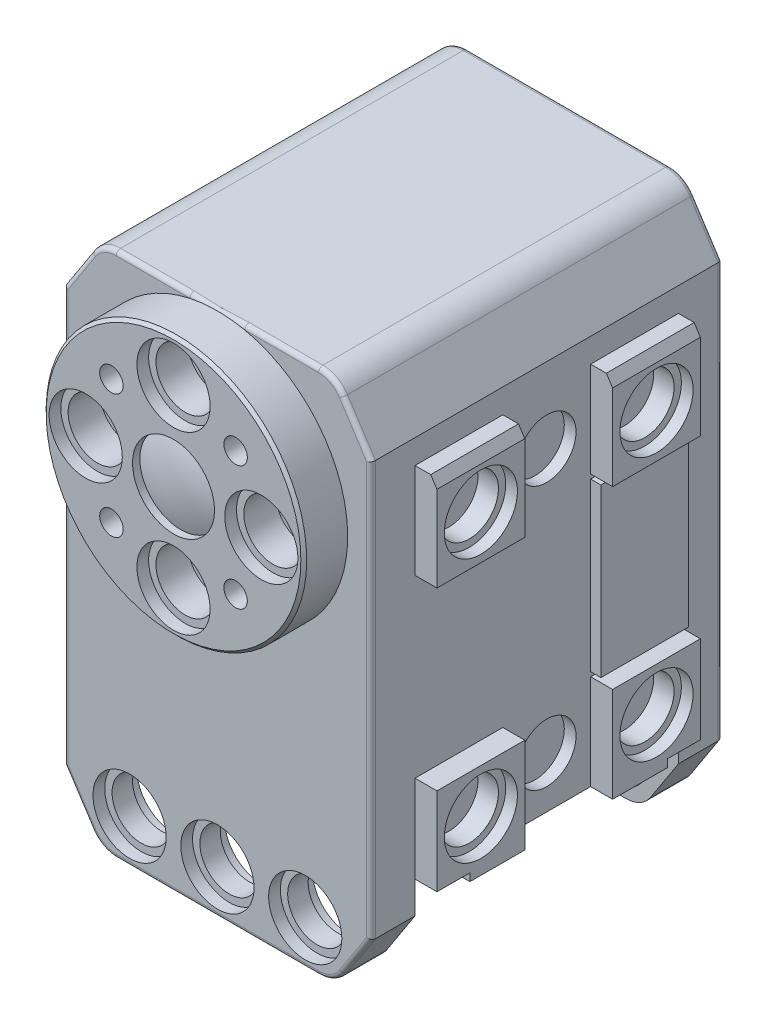
SolidWorks part; units mm, degrees
ref_plane "Front Plane" through (0, 0, 0) normal (0, 0, 1) x (1, 0, 0)
ref_plane "Top Plane" through (0, 0, 0) normal (0, 1, 0) x (1, 0, 0)
ref_plane "Right Plane" through (0, 0, 0) normal (1, 0, 0) x (0, 0, -1)
ref_plane "Plane1" through (0, 0, 0) normal (0, -1, 0) x (1, 0, 0)
sketch "Sketch1" plane through (0, 0, 0) normal (0, -1, 0) x (1, 0, 0)
  line L0 (0, 15) -> (0, 12)
  line L1 (0, 12) -> (8.9, 12)
  line L2 (8.9, 12) -> (8.9, 15)
  line L3 (8.9, 15) -> (2.8, 15)
  line L4 (2.8, 15) -> (2.8, 14.5)
  line L5 (0, 15.0001) -> (0, 12) construction
  arc A0 (2.8, 14.5) -> (0, 15) centre (0, 6.91) ccw
revolve "Revolve1" add sketch "Sketch1" angle 360 about L5
ref_plane "Plane2" through (0, 0, 12) normal (0, 0, 1) x (1, 0, 0)
sketch "Sketch2" plane through (0, 0, 12) normal (0, 0, 1) x (1, 0, 0)
  line L0 (10.5, -23.1503) -> (10.5, 5.1503)
  line L1 (10.5, 5.1503) -> (8, 9)
  line L2 (8, 9) -> (-8, 9)
  line L3 (-8, 9) -> (-10.5, 5.1503)
  line L4 (-10.5, 5.1503) -> (-10.5, -23.1503)
  line L5 (-10.5, -23.1503) -> (-8, -27)
  line L6 (-8, -27) -> (8, -27)
  line L7 (8, -27) -> (10.5, -23.1503)
extrude "Boss-Extrude1" add sketch "Sketch2" against normal blind 18.75
sketch "Sketch3" plane through (0, 0, -6.75) normal (0, 0, -1) x (-1, 0, 0)
  line L0 (-6, -21.5) -> (-10.5, -21.5)
  line L1 (-10.5, -21.5) -> (-10.5, -23.1503)
  line L2 (-10.5, -23.1503) -> (-8, -27)
  line L3 (-8, -27) -> (8, -27)
  line L4 (8, -27) -> (10.5, -23.1503)
  line L5 (10.5, -23.1503) -> (10.5, -21.5)
  line L6 (10.5, -21.5) -> (6, -21.5)
  line L7 (4, -22.5) -> (-4, -22.5)
  arc A0 (6, -21.5) -> (4, -22.5) centre (6, -24) ccw
  arc A1 (-4, -22.5) -> (-6, -21.5) centre (-6, -24) ccw
extrude "Cut-Extrude1" cut sketch "Sketch3" against normal blind 13.5
sketch "Sketch4" plane through (0, 0, 6.75) normal (0, 0, -1) x (-1, 0, 0)
  line L0 (-6, -20.975) -> (-10.5, -20.975)
  line L1 (-10.5, -20.975) -> (-10.5, -23.1503)
  line L2 (-10.5, -23.1503) -> (-8, -27)
  line L3 (-8, -27) -> (8, -27)
  line L4 (8, -27) -> (10.5, -23.1503)
  line L5 (10.5, -23.1503) -> (10.5, -20.975)
  line L6 (10.5, -20.975) -> (6, -20.975)
  line L7 (3.3731, -22.5) -> (-3.3731, -22.5)
  arc A0 (-3.3731, -22.5) -> (-6, -20.975) centre (-6, -24) ccw
  arc A1 (6, -20.975) -> (3.3731, -22.5) centre (6, -24) ccw
extrude "Cut-Extrude2" cut sketch "Sketch4" against normal blind 2.25
sketch "Sketch5" plane through (10.5, 0, 0) normal (1, 0, 0) x (0, 0, -1)
  line L0 (6.75, 5.1503) -> (6.75, -21.5)
  line L1 (6.75, -21.5) -> (3, -21.5)
  line L2 (3, -21.5) -> (3, 5.1503)
  line L3 (3, 5.1503) -> (6.75, 5.1503)
extrude "Boss-Extrude2" add sketch "Sketch5" along normal blind 1.5
sketch "Sketch6" plane through (10.5, 0, 0) normal (1, 0, 0) x (0, 0, -1)
  line L0 (-9, -20.975) -> (-9, -15)
  line L1 (-9, -15) -> (-3, -15)
  line L2 (-3, -15) -> (-3, -21.5)
  line L3 (-3, -21.5) -> (-6.75, -21.5)
  line L4 (-6.75, -21.5) -> (-6.75, -20.975)
  line L5 (-6.75, -20.975) -> (-9, -20.975)
extrude "Boss-Extrude3" add sketch "Sketch6" along normal blind 1.5
sketch "Sketch7" plane through (-10.5, 0, 0) normal (-1, 0, 0) x (0, 0, 1)
  line L0 (9, -15) -> (9, -20.975)
  line L1 (9, -20.975) -> (6.75, -20.975)
  line L2 (6.75, -20.975) -> (6.75, -21.5)
  line L3 (6.75, -21.5) -> (3, -21.5)
  line L4 (3, -21.5) -> (3, -15)
  line L5 (3, -15) -> (9, -15)
extrude "Boss-Extrude4" add sketch "Sketch7" along normal blind 1.5
sketch "Sketch8" plane through (-10.5, 0, 0) normal (-1, 0, 0) x (0, 0, 1)
  line L0 (-3, 5.1503) -> (-3, -21.5)
  line L1 (-3, -21.5) -> (-6.75, -21.5)
  line L2 (-6.75, -21.5) -> (-6.75, 5.1503)
  line L3 (-6.75, 5.1503) -> (-3, 5.1503)
extrude "Boss-Extrude5" add sketch "Sketch8" along normal blind 1.5
sketch "Sketch9" plane through (0, 5.1503, 0) normal (0, 1, 0) x (-1, 0, 0)
  line L0 (-12, -3) -> (-12, -6.75)
  line L1 (-12, -6.75) -> (-10.5, -6.75)
  line L2 (-10.5, -6.75) -> (-10.5, -3)
  line L3 (-10.5, -3) -> (-12, -3)
extrude "Cut-Extrude3" cut sketch "Sketch9" against normal blind 20.1503
sketch "Sketch10" plane through (0, 5.1503, 0) normal (0, 1, 0) x (-1, 0, 0)
  line L0 (10.5, -3) -> (10.5, -6.75)
  line L1 (10.5, -6.75) -> (12, -6.75)
  line L2 (12, -6.75) -> (12, -3)
  line L3 (12, -3) -> (10.5, -3)
extrude "Cut-Extrude4" cut sketch "Sketch10" against normal blind 20.1503
sketch "Sketch11" plane through (0, 0, -6.75) normal (0, 0, -1) x (-1, 0, 0)
  line L0 (12, -20.975) -> (6, -20.975)
  line L1 (3.3731, -22.5) -> (-3.3731, -22.5)
  line L2 (-6, -20.975) -> (-12, -20.975)
  line L3 (-12, -20.975) -> (-12, -15)
  line L4 (-12, -15) -> (-10.5, -15)
  line L5 (-10.5, -15) -> (-10.5, 5.1503)
  line L6 (-10.5, 5.1503) -> (-8, 9)
  line L7 (-8, 9) -> (8, 9)
  line L8 (8, 9) -> (10.5, 5.1503)
  line L9 (10.5, 5.1503) -> (10.5, -15)
  line L10 (10.5, -15) -> (12, -15)
  line L11 (12, -15) -> (12, -20.975)
  arc A0 (6, -20.975) -> (3.3731, -22.5) centre (6, -24) ccw
  arc A1 (-3.3731, -22.5) -> (-6, -20.975) centre (-6, -24) ccw
extrude "Boss-Extrude6" add sketch "Sketch11" along normal blind 2.25
sketch "Sketch12" plane through (0, 0, -9) normal (0, 0, -1) x (-1, 0, 0)
  line L0 (-8, 9) -> (8, 9)
  line L1 (8, 9) -> (10.5, 5.1503)
  line L2 (10.5, 5.1503) -> (10.5, -23.1503)
  line L3 (10.5, -23.1503) -> (8, -27)
  line L4 (8, -27) -> (-8, -27)
  line L5 (-8, -27) -> (-10.5, -23.1503)
  line L6 (-10.5, -23.1503) -> (-10.5, 5.1503)
  line L7 (-10.5, 5.1503) -> (-8, 9)
extrude "Boss-Extrude7" add sketch "Sketch12" along normal blind 3
sketch "Sketch13" plane through (0, 0, -9) normal (0, 0, 1) x (1, 0, 0)
  circle A0 centre (-6, -24) radius 2.5
extrude "Cut-Extrude5" cut sketch "Sketch13" against normal blind 0.8
sketch "Sketch14" plane through (0, 0, -12) normal (0, 0, -1) x (-1, 0, 0)
  circle A0 centre (6, -24) radius 2.5
extrude "Cut-Extrude6" cut sketch "Sketch14" against normal blind 0.8
sketch "Sketch15" plane through (0, 0, -11.2) normal (0, 0, -1) x (-1, 0, 0)
  circle A0 centre (6, -24) radius 2
extrude "Cut-Extrude7" cut sketch "Sketch15" against normal up to next
hole_wizard "M4x0.7 Tapped Hole1" positions "Sketch17" profile "Sketch16" tap size "M4x0.7" standard "ANSI Metric"
sketch "Sketch17" plane through (0, 0, -9) normal (0, 0, 1) x (1, 0, 0)
  point P0 (0, -24)
sketch "Sketch16" plane through (0, -24, -9) normal (1, 0, 0) x (0, -1, 0)
  line L0 (0, 0) -> (0, 2.2)
  line L1 (0, 2.2) -> (2.5, 2.2)
  line L2 (2.5, 2.2) -> (2.5, 1.4)
  line L3 (2.5, 1.4) -> (2, 1.4)
  line L4 (2, 1.4) -> (2, 0)
  line L5 (2, 0) -> (0, 0)
  line L10 (0, 2.2) -> (-2.5, 2.2) construction
  line L11 (0, -6.35) -> (0, 107.95) construction
  dimension "Tap Drill Dia." = 5
  dimension "Tap Drill Depth" = 2.2
  dimension "Thread Major Dia." = 4
  dimension "Thread Depth" = 1.4
  dimension "Drill Angle" = 180
sketch "Sketch18" plane through (0, 0, -9) normal (0, 0, 1) x (1, 0, 0)
  circle A0 centre (6, -24) radius 2.5
extrude "Cut-Extrude8" cut sketch "Sketch18" against normal blind 0.8
sketch "Sketch19" plane through (0, 0, -12) normal (0, 0, -1) x (-1, 0, 0)
  circle A0 centre (-6, -24) radius 2.5
extrude "Cut-Extrude9" cut sketch "Sketch19" against normal blind 0.8
sketch "Sketch20" plane through (0, 0, -11.2) normal (0, 0, -1) x (-1, 0, 0)
  circle A0 centre (-6, -24) radius 2
extrude "Cut-Extrude10" cut sketch "Sketch20" against normal up to next
sketch "Sketch21" plane through (10.5, 0, 0) normal (1, 0, 0) x (0, 0, -1)
  line L0 (9, -3) -> (3, -3)
  line L1 (3, -3) -> (3, 3.5)
  line L2 (3, 3.5) -> (9, 3.5)
  line L3 (9, 3.5) -> (9, -3)
extrude "Boss-Extrude8" add sketch "Sketch21" along normal blind 1.5
sketch "Sketch22" plane through (10.5, 0, 0) normal (1, 0, 0) x (0, 0, -1)
  line L0 (-9, 3.5) -> (-3, 3.5)
  line L1 (-3, 3.5) -> (-3, -3)
  line L2 (-3, -3) -> (-9, -3)
  line L3 (-9, -3) -> (-9, 3.5)
extrude "Boss-Extrude9" add sketch "Sketch22" along normal blind 1.5
sketch "Sketch23" plane through (10.5, 0, 0) normal (1, 0, 0) x (0, 0, -1)
  line L0 (9, -14.7) -> (3, -14.7)
  line L1 (3, -14.7) -> (3, -3.3)
  line L2 (3, -3.3) -> (9, -3.3)
  line L3 (9, -3.3) -> (9, -14.7)
extrude "Boss-Extrude10" add sketch "Sketch23" along normal blind 0.7
sketch "Sketch24" plane through (-10.5, 0, 0) normal (-1, 0, 0) x (0, 0, 1)
  line L0 (-9, 3.5) -> (-3, 3.5)
  line L1 (-3, 3.5) -> (-3, -3)
  line L2 (-3, -3) -> (-9, -3)
  line L3 (-9, -3) -> (-9, 3.5)
extrude "Boss-Extrude11" add sketch "Sketch24" along normal blind 1.5
sketch "Sketch25" plane through (-10.5, 0, 0) normal (-1, 0, 0) x (0, 0, 1)
  line L0 (9, -3) -> (3, -3)
  line L1 (3, -3) -> (3, 3.5)
  line L2 (3, 3.5) -> (9, 3.5)
  line L3 (9, 3.5) -> (9, -3)
extrude "Boss-Extrude12" add sketch "Sketch25" along normal blind 1.5
sketch "Sketch26" plane through (-10.5, 0, 0) normal (-1, 0, 0) x (0, 0, 1)
  line L0 (-9, -3.3) -> (-3, -3.3)
  line L1 (-3, -3.3) -> (-3, -14.7)
  line L2 (-3, -14.7) -> (-9, -14.7)
  line L3 (-9, -14.7) -> (-9, -3.3)
extrude "Boss-Extrude13" add sketch "Sketch26" along normal blind 0.7
ref_plane "Plane3" through (0, -24, 0) normal (0, 1, 0) x (1, 0, 0)
sketch "Sketch27" plane through (0, -24, 0) normal (0, 1, 0) x (1, 0, 0)
  line L0 (8.5, -9) -> (6, -9)
  line L1 (6, -9) -> (6, -12)
  line L2 (6, -12) -> (8.5, -12)
  line L3 (8.5, -12) -> (8.5, -11.2)
  line L4 (8.5, -11.2) -> (8, -11.2)
  line L5 (8, -11.2) -> (8, -9.8)
  line L6 (8, -9.8) -> (8.5, -9.8)
  line L7 (8.5, -9.8) -> (8.5, -9)
  line L8 (6, -9) -> (6, -12) construction
revolve "Cut-Revolve1" cut sketch "Sketch27" angle 360 about L8
sketch "Sketch28" plane through (0, -24, 0) normal (0, 1, 0) x (1, 0, 0)
  line L0 (-3.5, -9) -> (-6, -9)
  line L1 (-6, -9) -> (-6, -12)
  line L2 (-6, -12) -> (-3.5, -12)
  line L3 (-3.5, -12) -> (-3.5, -11.2)
  line L4 (-3.5, -11.2) -> (-4, -11.2)
  line L5 (-4, -11.2) -> (-4, -9.8)
  line L6 (-4, -9.8) -> (-3.5, -9.8)
  line L7 (-3.5, -9.8) -> (-3.5, -9)
  line L8 (-6, -9) -> (-6, -12) construction
revolve "Cut-Revolve2" cut sketch "Sketch28" angle 360 about L8
sketch "Sketch29" plane through (0, -24, 0) normal (0, 1, 0) x (1, 0, 0)
  line L0 (2.5, -9) -> (0, -9)
  line L1 (0, -9) -> (0, -12)
  line L2 (0, -12) -> (2.5, -12)
  line L3 (2.5, -12) -> (2.5, -11.2)
  line L4 (2.5, -11.2) -> (2, -11.2)
  line L5 (2, -11.2) -> (2, -9.8)
  line L6 (2, -9.8) -> (2.5, -9.8)
  line L7 (2.5, -9.8) -> (2.5, -9)
  line L8 (0, -9) -> (0, -12) construction
revolve "Cut-Revolve3" cut sketch "Sketch29" angle 360 about L8
hole_wizard "CBORE for M3.5 Hex Head Machine Screw1" positions "Sketch31" profile "Sketch30" counterbore size "M3.5" standard "ANSI Metric"
sketch "Sketch31" plane through (0, 0, -12) normal (0, 0, -1) x (-1, 0, 0)
  point P0 (6, 0)
  point P1 (0, 0)
  point P2 (-6, 0)
sketch "Sketch30" plane through (-6, 0, -12) normal (1, 0, 0) x (0, 1, 0)
  line L0 (0, 0) -> (0, 3)
  line L1 (0, 3) -> (2, 3)
  line L2 (2, 3) -> (2, 0.8)
  line L3 (2, 0.8) -> (2.5, 0.8)
  line L4 (2.5, 0.8) -> (2.5, 0)
  line L5 (2.5, 0) -> (0, 0)
  line L10 (0, 3) -> (-2, 3) construction
  line L11 (0, -6.35) -> (0, 107.95) construction
  dimension "Hole Dia." = 4
  dimension "Hole Depth" = 3
  dimension "C'Bore Dia." = 5
  dimension "C'Bore Depth" = 0.8
  dimension "Drill Angle" = 180
hole_wizard "Ø4.0 (4) Diameter Hole1" positions "Sketch33" profile "Sketch32" hole size "Ø4.0" standard "ANSI Metric"
sketch "Sketch33" plane through (-10.5, 0, 0) normal (-1, 0, 0) x (0, 0, 1)
  point P0 (0, 0)
  point P1 (0, -18)
sketch "Sketch32" plane through (-10.5, 0, 0) normal (0, 1, 0) x (0, 0, 1)
  line L0 (0, 0) -> (0, 0.8)
  line L1 (0, 0.8) -> (2, 0.8)
  line L2 (2, 0.8) -> (2, 0)
  line L5 (2, 0) -> (0, 0)
  line L10 (0, 0.8) -> (-2, 0.8) construction
  line L11 (0, -6.35) -> (0, 107.95) construction
  dimension "Hole Dia." = 4
  dimension "Hole Depth" = 0.8
  dimension "Drill Angle" = 180
hole_wizard "Ø4.0 (4) Diameter Hole2" positions "Sketch35" profile "Sketch34" hole size "Ø4.0" standard "ANSI Metric"
sketch "Sketch35" plane through (10.5, 0, 0) normal (1, 0, 0) x (0, 0, -1)
  point P0 (0, 0)
  point P1 (0, -18)
sketch "Sketch34" plane through (10.5, 0, 0) normal (0, 1, 0) x (0, 0, -1)
  line L0 (0, 0) -> (0, 0.8)
  line L1 (0, 0.8) -> (2, 0.8)
  line L2 (2, 0.8) -> (2, 0)
  line L5 (2, 0) -> (0, 0)
  line L10 (0, 0.8) -> (-2, 0.8) construction
  line L11 (0, -6.35) -> (0, 107.95) construction
  dimension "Hole Dia." = 4
  dimension "Hole Depth" = 0.8
  dimension "Drill Angle" = 180
hole_wizard "CBORE for M3.5 Hex Head Machine Screw2" positions "Sketch37" profile "Sketch36" counterbore size "M3.5" standard "ANSI Metric"
sketch "Sketch37" plane through (-12, 0, 0) normal (-1, 0, 0) x (0, 0, 1)
  point P0 (6, -18)
  point P1 (-6, -18)
  point P2 (-6, 0)
  point P3 (6, 0)
sketch "Sketch36" plane through (-12, -18, 6) normal (0, 1, 0) x (0, 0, 1)
  line L0 (0, 0) -> (0, 2.2)
  line L1 (0, 2.2) -> (2, 2.2)
  line L2 (2, 2.2) -> (2, 0.8)
  line L3 (2, 0.8) -> (2.5, 0.8)
  line L4 (2.5, 0.8) -> (2.5, 0)
  line L5 (2.5, 0) -> (0, 0)
  line L10 (0, 2.2) -> (-2, 2.2) construction
  line L11 (0, -6.35) -> (0, 107.95) construction
  dimension "Hole Dia." = 4
  dimension "Hole Depth" = 2.2
  dimension "C'Bore Dia." = 5
  dimension "C'Bore Depth" = 0.8
  dimension "Drill Angle" = 180
hole_wizard "Ø1.6 (1.6) Diameter Hole1" positions "Sketch39" profile "Sketch38" hole size "Ø1.6" standard "ANSI Metric"
sketch "Sketch39" plane through (0, 0, 15) normal (0, 0, 1) x (1, 0, 0)
  point P0 (4.2426, 4.2426)
  point P1 (-4.2426, 4.2426)
  point P2 (4.2426, -4.2426)
  point P3 (-4.2426, -4.2426)
sketch "Sketch38" plane through (4.2426, 4.2426, 15) normal (1, 0, 0) x (0, -1, 0)
  line L0 (0, 0) -> (0, 3)
  line L1 (0, 3) -> (0.8, 3)
  line L2 (0.8, 3) -> (0.8, 0)
  line L5 (0.8, 0) -> (0, 0)
  line L10 (0, 3) -> (-0.8, 3) construction
  line L11 (0, -6.35) -> (0, 107.95) construction
  dimension "Hole Dia." = 1.6
  dimension "Hole Depth" = 3
  dimension "Drill Angle" = 180
hole_wizard "CBORE for M3.5 Hex Head Machine Screw3" positions "Sketch41" profile "Sketch40" counterbore size "M3.5" standard "ANSI Metric"
sketch "Sketch41" plane through (12, 0, 0) normal (1, 0, 0) x (0, 0, -1)
  point P0 (6, -18)
  point P1 (-6, -18)
  point P2 (6, 0)
  point P3 (-6, 0)
sketch "Sketch40" plane through (12, -18, -6) normal (0, 1, 0) x (0, 0, -1)
  line L0 (0, 0) -> (0, 2.2)
  line L1 (0, 2.2) -> (2, 2.2)
  line L2 (2, 2.2) -> (2, 0.8)
  line L3 (2, 0.8) -> (2.5, 0.8)
  line L4 (2.5, 0.8) -> (2.5, 0)
  line L5 (2.5, 0) -> (0, 0)
  line L10 (0, 2.2) -> (-2, 2.2) construction
  line L11 (0, -6.35) -> (0, 107.95) construction
  dimension "Hole Dia." = 4
  dimension "Hole Depth" = 2.2
  dimension "C'Bore Dia." = 5
  dimension "C'Bore Depth" = 0.8
  dimension "Drill Angle" = 180
hole_wizard "CBORE for M3.5 Hex Head Machine Screw4" positions "Sketch43" profile "Sketch42" counterbore size "M3.5" standard "ANSI Metric"
sketch "Sketch43" plane through (0, 0, 15) normal (0, 0, 1) x (1, 0, 0)
  point P0 (6, 0)
  point P1 (0, 6)
  point P2 (-6, 0)
  point P3 (0, -6)
sketch "Sketch42" plane through (6, 0, 15) normal (1, 0, 0) x (0, -1, 0)
  line L0 (0, 0) -> (0, 3)
  line L1 (0, 3) -> (2, 3)
  line L2 (2, 3) -> (2, 0.8)
  line L3 (2, 0.8) -> (2.5, 0.8)
  line L4 (2.5, 0.8) -> (2.5, 0)
  line L5 (2.5, 0) -> (0, 0)
  line L10 (0, 3) -> (-2, 3) construction
  line L11 (0, -6.35) -> (0, 107.95) construction
  dimension "Hole Dia." = 4
  dimension "Hole Depth" = 3
  dimension "C'Bore Dia." = 5
  dimension "C'Bore Depth" = 0.8
  dimension "Drill Angle" = 180
fillet "Fillet1" radius 2 6 edges at (8, -27, -10.5) (8, -27, 10.5) (8, 9, 0) (-8, 9, 0) (-8, -27, -10.5) (-8, -27, 10.5)
chamfer "Chamfer1" distance 0.6595 angle 33 4 edges at (12, 3.5, -6) (12, 3.5, 6) (-12, 3.5, -6) (-12, 3.5, 6)
chamfer "Chamfer4" distance 0.2 angle 45 1 edges at (-8.9, 0, 15)
fillet "Fillet2" radius 0.3 24 edges at (-9.5457, -24.6198, 12) (-7.8684, -26.7576, 12) (0, -27, 12) (7.8684, -26.7576, 12) (9.5457, -24.6198, 12) (10.5, -9, 12) (-10.5, -9, 12) (9.5457, 6.6198, 12) (7.8684, 8.7576, 12) (0, 9, 12) (-7.8684, 8.7576, 12) (-9.5457, 6.6198, 12) (9.5457, -24.6198, -12) (-9.5457, -24.6198, -12) (7.8684, -26.7576, -12) (-7.8684, -26.7576, -12) (0, -27, -12) (-10.5, -9, -12) (10.5, -9, -12) (-9.5457, 6.6198, -12) (9.5457, 6.6198, -12) (-7.8684, 8.7576, -12) (7.8684, 8.7576, -12) (0, 9, -12)
ref_plane "Plane4" through (0, 9, 0) normal (0, 1, 0) x (1, 0, 0)
sketch "Sketch58" plane through (0, 0, 15) normal (0, 0, 1) x (1, 0, 0)
  circle A0 centre (0, 0) radius 8.7
extrude "Boss-Extrude26" add sketch "Sketch58" along normal blind 45 separate body contours A0
sketch "Sketch60" plane through (0, 0, 15) normal (0, 0, -1) x (-1, 0, 0)
  circle A1 centre (-6, 0) radius 2
  circle A3 centre (0, -6) radius 2
  circle A4 centre (6, 0) radius 2
  circle A5 centre (0, 6) radius 2
extrude "Cut-Extrude17" cut sketch "Sketch60" against normal blind 7
sketch "Sketch61" plane through (0, 0, 60) normal (0, 0, 1) x (1, 0, 0)
  line L1 (-3.7873, -8.6983) -> (4.1327, -8.6983)
  line L2 (-3.7873, -8.6983) -> (-3.7873, -4.6983)
  line L3 (-3.7873, -4.6983) -> (4.1327, -4.6983)
  line L4 (4.1327, -8.6983) -> (4.1327, -4.6983)
  circle A1 centre (0, 0) radius 8.7 construction
  point P4 (0.1727, -8.6983)
  dimension "D1" = 7.92
  dimension "D2" = 4
extrude "Boss-Extrude27" add sketch "Sketch61" against normal blind 10 separate body contours L3 L4 L1 L2
fillet "Fillet5" radius 0.4 3 edges at (4.1327, -8.6983, 55) (0.1727, -8.6983, 50) (-3.7873, -8.6983, 55)
delete or keep bodies "Body-Delete/Keep 1" type delete bodies bodies 164 163
